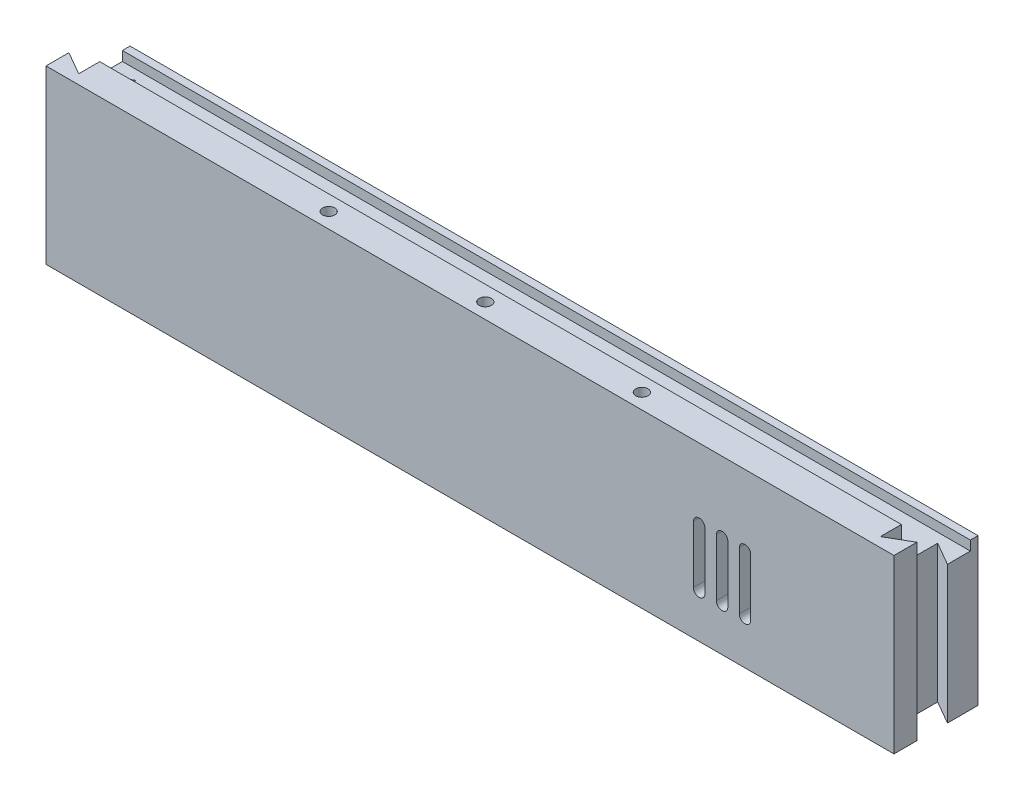
SolidWorks part; units mm, degrees
ref_plane "前视基准面" through (0, 0, 0) normal (0, 0, 1) x (1, 0, 0)
ref_plane "上视基准面" through (0, 0, 0) normal (0, 1, 0) x (1, 0, 0)
ref_plane "右视基准面" through (0, 0, 0) normal (1, 0, 0) x (0, 0, -1)
sketch "草图1" plane through (0, 0, 0) normal (0, 1, 0) x (1, 0, 0)
  line L1 (0, 0) -> (250, 0)
  line L2 (0, 0) -> (0, 350)
  line L3 (0, 350) -> (250, 350)
  line L4 (250, 0) -> (250, 350)
  line L12 (0, 350) -> (-1.1314, 351.1314)
  line L13 (-10, -10) -> (260, -10)
  line L14 (-10, -10) -> (-10, 360)
  line L15 (-10, 360) -> (260, 360)
  line L16 (260, -10) -> (260, 360)
  line L18 (14, 14) -> (236, 14)
  line L19 (14, 14) -> (14, 336)
  line L20 (14, 336) -> (236, 336)
  line L21 (236, 14) -> (236, 336)
  dimension "D7" = 135
  dimension "D1" = 350
  dimension "D2" = 250
  dimension "D3" = 10
  dimension "D4" = 10
  dimension "D5" = 10
  dimension "D6" = 10
  dimension "D8" = 14
  dimension "D9" = 14
  dimension "D10" = 14
  dimension "D11" = 14
extrude "凸台-拉伸2" add sketch "草图1" along normal blind 45
ref_plane "基准面1" through (0, 38.5, 0) normal (0, 1, 0) x (1, 0, 0)
sketch "草图4" plane through (0, 38.5, 0) normal (0, 1, 0) x (1, 0, 0)
  line L0 (0, 0) -> (250, 0) construction
  line L1 (0, 350) -> (250, 350) construction
  line L2 (250, 0) -> (250, 350) construction
  line L3 (0, 0) -> (0, 350) construction
  line L4 (0, 0) -> (250, 0)
  line L5 (0, 350) -> (250, 350)
  line L6 (250, 0) -> (250, 350)
  line L7 (0, 0) -> (0, 350)
  line L9 (14, 14) -> (236, 14)
  line L10 (14, 14) -> (14, 336)
  line L11 (14, 336) -> (236, 336)
  line L12 (236, 14) -> (236, 336)
  dimension "D1" = 14
  dimension "D2" = 14
  dimension "D3" = 14
  dimension "D4" = 14
extrude "凸台-拉伸3" add sketch "草图4" against normal blind 5
sketch "草图9" plane through (0, 38.5, 0) normal (0, 1, 0) x (1, 0, 0)
  line L0 (236, 336) -> (14, 336) construction
  line L1 (236, 14) -> (236, 336) construction
  line L2 (14, 14) -> (236, 14) construction
  line L3 (14, 336) -> (14, 14) construction
  line L4 (0, 350) -> (0, 0)
  line L5 (0, 0) -> (250, 0)
  line L6 (250, 0) -> (250, 350)
  line L7 (250, 350) -> (0, 350)
  line L8 (0, 350) -> (0, 0)
  line L9 (0, 0) -> (250, 0)
  line L10 (250, 0) -> (250, 350)
  line L11 (250, 350) -> (0, 350)
  line L12 (236, 336) -> (14, 336)
  line L13 (236, 14) -> (236, 336)
  line L14 (14, 14) -> (236, 14)
  line L15 (14, 336) -> (14, 14)
  line L16 (238, 12) -> (238, 338)
  line L17 (238, 338) -> (12, 338)
  line L18 (12, 338) -> (12, 12)
  line L19 (12, 12) -> (238, 12)
  line L20 (2, 348) -> (2, 2)
  line L21 (2, 2) -> (248, 2)
  line L22 (248, 2) -> (248, 348)
  line L23 (248, 348) -> (2, 348)
  dimension "D1" = 0
  dimension "D2" = 2
  dimension "D3" = 2
extrude "切除-拉伸3" cut sketch "草图9" against normal blind 2.5 contours L22 L23 L20 L21 L19 L18 L17 L16
sketch "草图12" plane through (0, 45, 0) normal (0, 1, 0) x (1, 0, 0)
  line L0 (0, 350) -> (-10, 360)
  line L1 (-10, 175) -> (260, 175)
  line L2 (-10, -10) -> (-10, 360) construction
  line L3 (260, -10) -> (260, 360) construction
  line L4 (125, -10) -> (125, 360)
  line L5 (-10, -10) -> (260, -10) construction
  line L6 (-10, 360) -> (260, 360) construction
  circle A0 centre (-5, 355) radius 1.6
  circle A1 centre (-5, -5) radius 1.6
  circle A2 centre (255, -5) radius 1.6
  circle A3 centre (255, 355) radius 1.6
  dimension "D1" = 3.2
extrude "切除-拉伸5" cut sketch "草图12" against normal blind 109.5 contours A1 | L0 A0 | L0 A0 | A3 | A2
fillet "圆角1" radius 5 4 edges at (260, 22.5, -360) (260, 22.5, 10) (-10, 22.5, 10) (-10, 22.5, -360)
sketch "草图13" plane through (0, 33.5, 0) normal (0, -1, 0) x (1, 0, 0)
  line L0 (14, -336) -> (14, -14) construction
  line L1 (236, -336) -> (14, -336) construction
  line L2 (14, -14) -> (236, -14) construction
  line L3 (236, -14) -> (236, -336) construction
  line L4 (0, 0) -> (0, -350)
  line L5 (0, -350) -> (250, -350)
  line L6 (250, -350) -> (250, 0)
  line L7 (250, 0) -> (0, 0)
  line L8 (0, 0) -> (0, -350)
  line L9 (0, -350) -> (250, -350)
  line L10 (250, -350) -> (250, 0)
  line L11 (250, 0) -> (0, 0)
  line L12 (14, -336) -> (14, -14)
  line L13 (236, -336) -> (14, -336)
  line L14 (14, -14) -> (236, -14)
  line L15 (236, -14) -> (236, -336)
  dimension "D1" = 0
extrude "凸台-拉伸4" add sketch "草图13" along normal blind 33.5
sketch "草图14" plane through (0, 0, 0) normal (0, -1, 0) x (1, 0, 0)
  line L0 (14, -14) -> (14, 10)
  line L1 (-5, 10) -> (255, 10) construction
  line L2 (236, -14) -> (236, 10)
  line L3 (14, 2) -> (20.0622, 5.5)
  line L4 (20.0622, 5.5) -> (20.0622, -9.5)
  line L5 (20.0622, -9.5) -> (14, -6)
  line L6 (125, 10) -> (125, -14)
  line L7 (236, -14) -> (14, -14) construction
  line L8 (236, 2) -> (229.9378, 5.5)
  line L9 (229.9378, -9.5) -> (236, -6)
  line L10 (229.9378, 5.5) -> (229.9378, -9.5)
  line L15 (-5, -360) -> (255, -360)
  line L16 (260, -355) -> (260, 5)
  line L17 (255, 10) -> (-5, 10)
  line L18 (-10, 5) -> (-10, -355)
  line L19 (-5, -360) -> (255, -360)
  line L20 (260, -355) -> (260, 5)
  line L21 (255, 10) -> (-5, 10)
  line L22 (-10, 5) -> (-10, -355)
  arc A4 (255, -360) -> (260, -355) centre (255, -355) ccw
  arc A5 (260, 5) -> (255, 10) centre (255, 5) ccw
  arc A6 (-5, 10) -> (-10, 5) centre (-5, 5) ccw
  arc A7 (-10, -355) -> (-5, -360) centre (-5, -355) ccw
  arc A8 (255, -360) -> (260, -355) centre (255, -355) ccw
  arc A9 (260, 5) -> (255, 10) centre (255, 5) ccw
  arc A10 (-5, 10) -> (-10, 5) centre (-5, 5) ccw
  arc A11 (-10, -355) -> (-5, -360) centre (-5, -355) ccw
  point P10 (14, -2)
  circle M14 centre (-5, -355) radius 1.6
  circle M15 centre (-5, 5) radius 1.6
  line M16 (-5, -360) -> (255, -360)
  arc M17 (255, -360) -> (260, -355) centre (255, -355) ccw
  line M18 (260, -355) -> (260, 5)
  arc M19 (260, 5) -> (255, 10) centre (255, 5) ccw
  line M20 (255, 10) -> (-5, 10)
  arc M21 (-5, 10) -> (-10, 5) centre (-5, 5) ccw
  line M22 (-10, 5) -> (-10, -355)
  arc M23 (-10, -355) -> (-5, -360) centre (-5, -355) ccw
  circle M24 centre (255, -355) radius 1.6
  circle M25 centre (255, 5) radius 1.6
  line M26 (236, -14) -> (236, -336)
  line M27 (236, -336) -> (14, -336)
  line M28 (14, -336) -> (14, -14)
  dimension "D1" = 4
  dimension "D2" = 4
  dimension "D3" = 60
  dimension "D4" = 60
  dimension "D5" = 15
  dimension "D6" = 0
extrude "切除-拉伸8" cut sketch "草图14" against normal blind 126.5 contours L2 L0 M26 M27 M28 M20 M21 M22 M23 M16 M17 M18 M19 M15 M24 M25 M14 | L5 L4 L3 L0 | M15 | L8 L10 L9 L2 | M25 | M24 | M14
sketch "草图15" plane through (0, 38.5, 0) normal (0, 1, 0) x (1, 0, 0)
  line L4 (20.0622, 0) -> (229.9378, 0)
  line L5 (229.9378, 0) -> (229.9378, 2)
  line L6 (229.9378, 2) -> (20.0622, 2)
  line L7 (20.0622, 2) -> (20.0622, 0)
  line L8 (20.0622, 0) -> (229.9378, 0)
  line L9 (229.9378, 0) -> (229.9378, 2)
  line L10 (229.9378, 2) -> (20.0622, 2)
  line L11 (20.0622, 2) -> (20.0622, 0)
  dimension "D1" = 0
extrude "切除-拉伸9" cut sketch "草图15" against normal blind 2.5
sketch "草图16" plane through (0, 45, 0) normal (0, 1, 0) x (1, 0, 0)
  line L13 (229.9378, -5.5) -> (229.9378, 0)
  line L14 (229.9378, 0) -> (20.0622, 0)
  line L15 (20.0622, 0) -> (20.0622, -5.5)
  line L16 (20.0622, -5.5) -> (14, -2)
  line L17 (14, -2) -> (14, -10)
  line L18 (14, -10) -> (236, -10)
  line L19 (236, -10) -> (236, -2)
  line L20 (236, -2) -> (229.9378, -5.5)
  line L21 (229.9378, -5.5) -> (229.9378, 0)
  line L22 (229.9378, 0) -> (20.0622, 0)
  line L23 (20.0622, 0) -> (20.0622, -5.5)
  line L24 (20.0622, -5.5) -> (14, -2)
  line L25 (14, -2) -> (14, -10)
  line L26 (14, -10) -> (236, -10)
  line L27 (236, -10) -> (236, -2)
  line L28 (236, -2) -> (229.9378, -5.5)
  line L29 (236, -8) -> (14, -8)
  line L37 (229.6077, -8) -> (234, -8)
  line L38 (234, -8) -> (234, -5.4641)
  line L39 (234, -5.4641) -> (229.6077, -8)
  line L40 (229.6077, -8) -> (234, -8)
  line L41 (234, -8) -> (234, -5.4641)
  line L42 (234, -5.4641) -> (229.6077, -8)
  line M17 (14, -10) -> (236, -10)
  line M18 (236, -10) -> (236, -2)
  dimension "D1" = 0
  dimension "D2" = 2
extrude "切除-拉伸10" cut sketch "草图16" against normal blind 60.5 contours L29 L25 M18 M17
sketch "草图18" plane through (0, 45, 0) normal (0, 1, 0) x (1, 0, 0)
  line L0 (236, -4) -> (166, -4)
  line L1 (236, -8) -> (236, -2) construction
  line L2 (236, -8) -> (14, -8) construction
  line L3 (125, -8) -> (125, 5.7143)
  circle A0 centre (166, -4) radius 1.6
  circle A1 centre (84, -4) radius 1.6
  dimension "D3" = 3.2
  dimension "D1" = 4
  dimension "D2" = 70
extrude "切除-拉伸11" cut sketch "草图18" against normal blind 60.5
sketch "草图19" plane through (0, 0, 0) normal (0, -1, 0) x (1, 0, 0)
  line L0 (206, -14) -> (206, -8)
  line L1 (236, -14) -> (14, -14) construction
  line L2 (206, -8) -> (176, -8)
  line L3 (176, -8) -> (176, -14)
  line L4 (236, -14) -> (236, -6) construction
  line L5 (206, -14) -> (176, -14)
  dimension "D1" = 6
  dimension "D2" = 30
  dimension "D3" = 30
extrude "切除-拉伸12" cut sketch "草图19" against normal blind 30
sketch "草图20" plane through (0, 0, -8) normal (0, 0, -1) x (-1, 0, 0)
  line L0 (-181, 30) -> (-181, 8)
  line L1 (-181, 8) -> (-201, 8)
  line L2 (-201, 8) -> (-201, 30)
  line L3 (-191, 8) -> (-191, 30)
  line L4 (-206, 0) -> (-176, 0)
  line L5 (-176, 0) -> (-176, 30)
  line L6 (-176, 30) -> (-206, 30)
  line L7 (-206, 30) -> (-206, 0)
  line L8 (-206, 0) -> (-176, 0)
  line L9 (-176, 0) -> (-176, 30)
  line L10 (-176, 30) -> (-206, 30)
  line L11 (-206, 30) -> (-206, 0)
  line L12 (-197, 11.5) -> (-197, 26.5) construction
  line L13 (-198.5, 11.5) -> (-198.5, 26.5)
  line L14 (-195.5, 11.5) -> (-195.5, 26.5)
  line L15 (-201, 19) -> (-181, 19)
  line L16 (-191, 11.5) -> (-191, 26.5) construction
  line L17 (-192.5, 11.5) -> (-192.5, 26.5)
  line L18 (-189.5, 11.5) -> (-189.5, 26.5)
  line L19 (-185, 11.5) -> (-185, 26.5) construction
  line L20 (-186.5, 11.5) -> (-186.5, 26.5)
  line L21 (-183.5, 11.5) -> (-183.5, 26.5)
  arc A0 (-198.5, 11.5) -> (-195.5, 11.5) centre (-197, 11.5) ccw
  arc A1 (-195.5, 26.5) -> (-198.5, 26.5) centre (-197, 26.5) ccw
  arc A2 (-192.5, 11.5) -> (-189.5, 11.5) centre (-191, 11.5) ccw
  arc A3 (-189.5, 26.5) -> (-192.5, 26.5) centre (-191, 26.5) ccw
  arc A4 (-186.5, 11.5) -> (-183.5, 11.5) centre (-185, 11.5) ccw
  arc A5 (-183.5, 26.5) -> (-186.5, 26.5) centre (-185, 26.5) ccw
  point P12 (-197, 19)
  point P22 (-191, 19)
  point P29 (-185, 19)
  dimension "D6" = 1.5
  dimension "D2" = 20
  dimension "D3" = 22
  dimension "D4" = 90
  dimension "D5" = 15
  dimension "D7" = 4
  dimension "D9" = 4
  dimension "D1" = 0
  dimension "D8" = 3
extrude "切除-拉伸13" cut sketch "草图20" against normal blind 30 contours L14 A1 L13 L15 | L13 A0 L14 L15 | L17 A2 L3 L15 | L3 A2 L18 L15 | L18 A3 L3 L15 | L3 A3 L17 L15 | L21 A5 L20 L15 | L20 A4 L21 L15
sketch "草图22" plane through (0, 45, 0) normal (0, 1, 0) x (1, 0, 0)
  line L0 (125, 0) -> (125, -8)
  line L1 (20.0622, 0) -> (229.9378, 0) construction
  line L2 (236, -8) -> (14, -8) construction
  circle A0 centre (125, -4) radius 1.6
  dimension "D1" = 3.2
extrude "切除-拉伸14" cut sketch "草图22" against normal blind 55 contours L0 A0 | L0 A0
equation "\"2。5\"=10"
